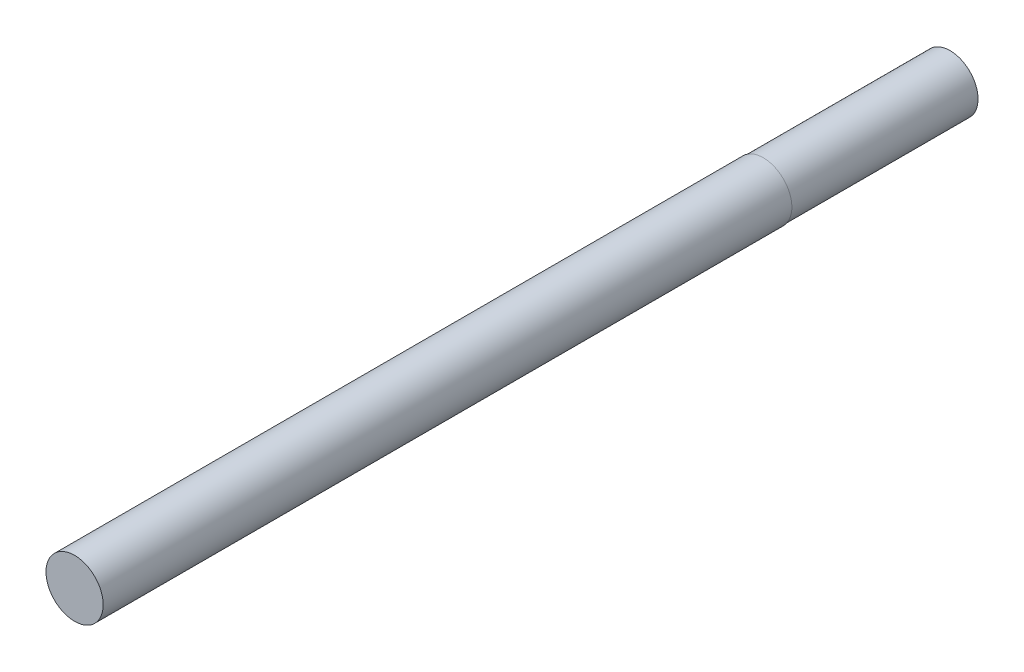
SolidWorks part; units mm, degrees
ref_plane "前视基准面" through (0, 0, 0) normal (0, 0, 1) x (1, 0, 0)
ref_plane "上视基准面" through (0, 0, 0) normal (0, 1, 0) x (1, 0, 0)
ref_plane "右视基准面" through (0, 0, 0) normal (1, 0, 0) x (0, 0, -1)
sketch "草图2" plane through (0, 0, 0) normal (0, 0, 1) x (1, 0, 0)
  circle A0 centre (0, 0) radius 2.45
  dimension "D1" = 4.9
extrude "凸台-拉伸1" add sketch "草图2" along normal blind 75
sketch "草图4" plane through (0, 0, 0) normal (0, 0, -1) x (-1, 0, 0)
  circle A0 centre (0, 0) radius 2.45
  circle A1 centre (0, 0) radius 2.4
  dimension "D1" = 4.8
  dimension "D2" = 4.9
extrude "切除-拉伸2" cut sketch "草图4" against normal blind 16
cosmetic thread "装饰螺纹线1" parameters "D2"=3.5
